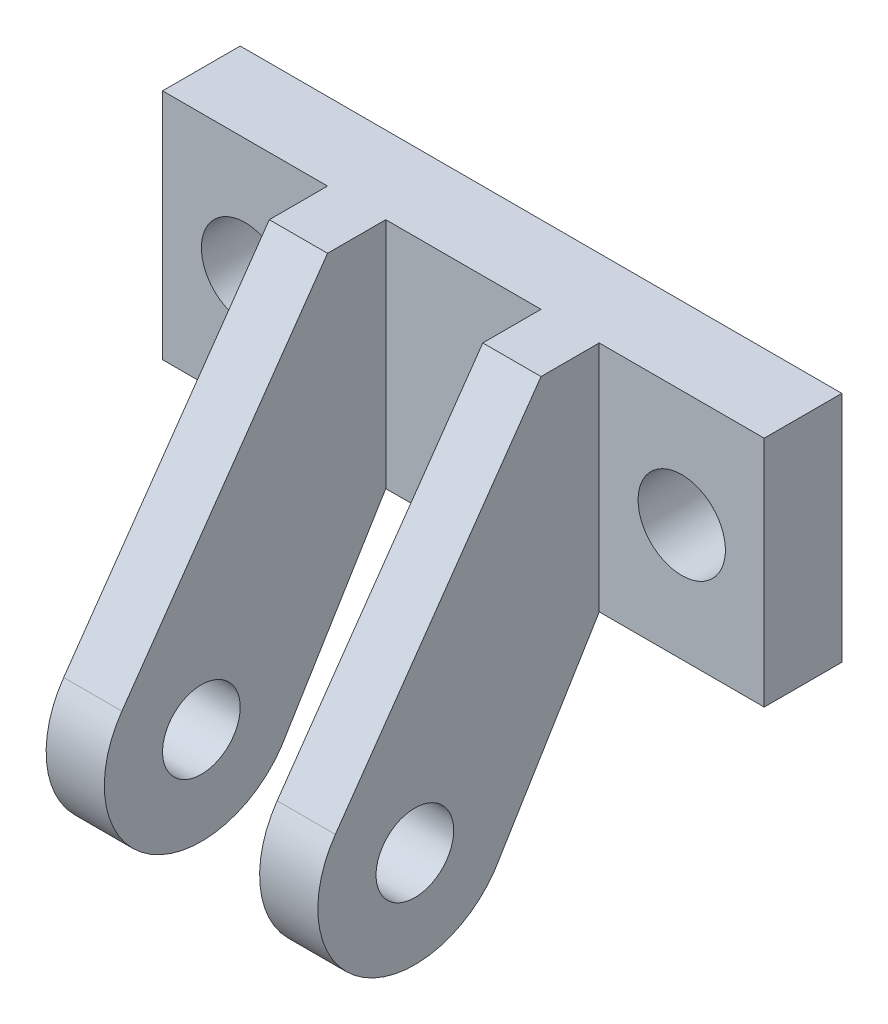
SolidWorks part; units mm, degrees
ref_plane "前视基准面" through (0, 0, 0) normal (0, 0, 1) x (1, 0, 0)
ref_plane "上视基准面" through (0, 0, 0) normal (0, 1, 0) x (1, 0, 0)
ref_plane "右视基准面" through (0, 0, 0) normal (1, 0, 0) x (0, 0, -1)
sketch "草图1" plane through (0, 0, 0) normal (0, 0, 1) x (1, 0, 0)
  line L0 (0, 0) -> (0, -4.2732) construction
  line L1 (31, -12) -> (-31, -12)
  line L2 (31, -12) -> (31, 12)
  line L3 (31, 12) -> (-31, 12)
  line L4 (-31, -12) -> (-31, 12)
  line L5 (31, -12) -> (-31, 12) construction
  line L6 (31, 12) -> (-31, -12) construction
  circle A0 centre (-22.5, 0) radius 4.5
  circle A2 centre (22.5, 0) radius 4.5
  point P0 (0, 0)
  dimension "D3" = 9
  dimension "D1" = 62
  dimension "D2" = 24
  dimension "D4" = 45
extrude "凸台-拉伸1" add sketch "草图1" along normal blind 8
sketch "草图2" plane through (0, 0, 0) normal (1, 0, 0) x (0, 0, -1)
  line L0 (-8, 12) -> (-14, 12)
  line L1 (-14, 12) -> (-35.1915, -18.2642)
  line L2 (-8, -12) -> (-18.8085, -29.7358)
  line L3 (0, -12) -> (0, 12) construction
  line L4 (-8, 12) -> (0, 12) construction
  line L8 (0, -12) -> (0, 12)
  line L9 (0, 12) -> (-8, 12)
  line L10 (-8, 12) -> (-8, -12)
  line L11 (-8, -12) -> (0, -12)
  line L12 (0, -12) -> (0, 12)
  line L13 (0, 12) -> (-8, 12)
  line L15 (-8, -12) -> (0, -12)
  arc A0 (-35.1915, -18.2642) -> (-18.8085, -29.7358) centre (-27, -24) ccw
  point P8 (0, 0)
  point P11 (0, 0)
  point P13 (0, 0)
  dimension "D2" = 10
  dimension "D1" = 27
  dimension "D3" = 14
  dimension "D4" = 180
  dimension "D6" = 36
  dimension "D5" = 0
extrude "凸台-拉伸2" add sketch "草图2" along normal mid plane 28
sketch "草图5" plane through (0, 0, 0) normal (1, 0, 0) x (0, 0, -1)
  line L4 (-18.8085, -29.7358) -> (-8, -12)
  line L5 (-8, -12) -> (-8, 12)
  line L6 (-8, 12) -> (-14, 12)
  line L7 (-14, 12) -> (-35.1915, -18.2642)
  line L8 (-18.8085, -29.7358) -> (-8, -12)
  line L9 (-8, -12) -> (-8, 12)
  line L10 (-8, 12) -> (-14, 12)
  line L11 (-14, 12) -> (-35.1915, -18.2642)
  arc A1 (-35.1915, -18.2642) -> (-18.8085, -29.7358) centre (-27, -24) ccw
  arc A2 (-35.1915, -18.2642) -> (-18.8085, -29.7358) centre (-27, -24) ccw
  dimension "D1" = 0
extrude "切除-拉伸2" cut sketch "草图5" against normal mid plane 16
sketch "草图6" plane through (14, 0, 0) normal (1, 0, 0) x (0, 0, -1)
  circle A1 centre (-27, -24) radius 4
  point P1 (-54.5308, -3.9977)
  dimension "D1" = 8
extrude "切除-拉伸3" cut sketch "草图6" against normal through all both and the other way through all
